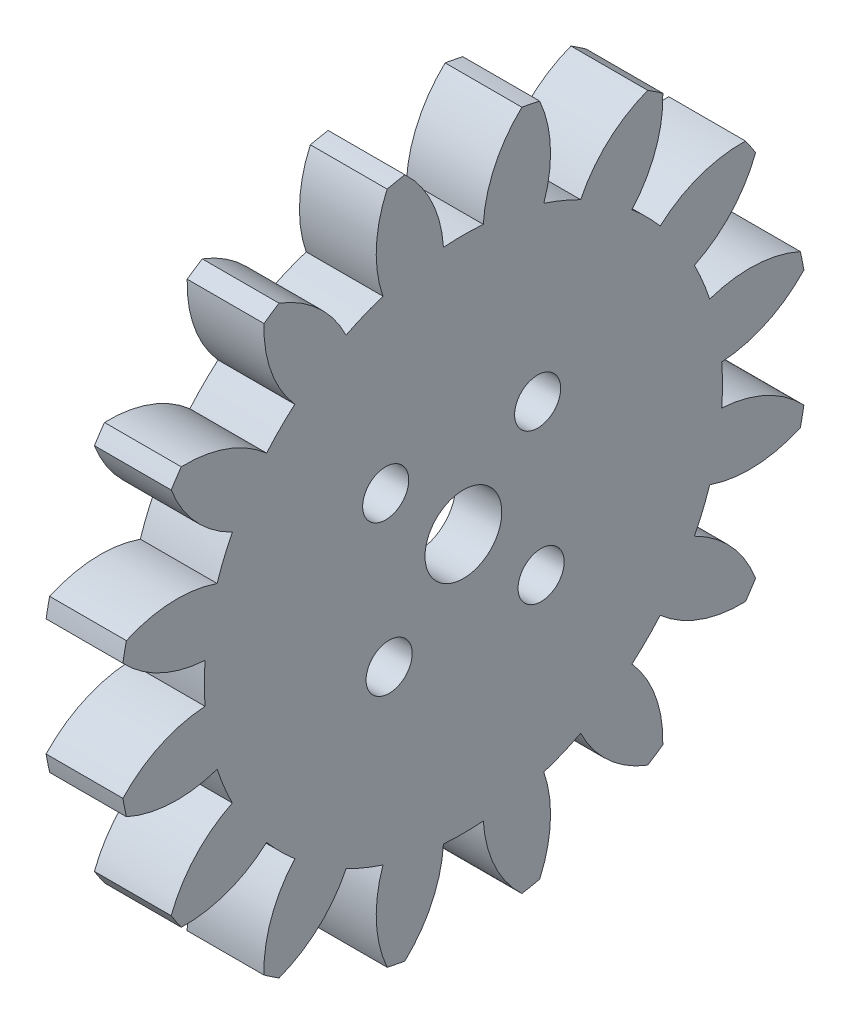
SolidWorks part; units mm, degrees
ref_plane "Plane1" through (0, 0, 0) normal (0, 0, 1) x (1, 0, 0)
ref_plane "Plane2" through (0, 0, 0) normal (0, 1, 0) x (1, 0, 0)
ref_plane "Plane3" through (0, 0, 0) normal (1, 0, 0) x (0, 0, -1)
other "Configuration Table"
sketch "HoldingSke" plane through (0, 0, 0) normal (0, 1, 0) x (1, 0, 0)
  line L0 (0, 0) -> (0.3845, -0.1103)
  line L1 (-15, 0) -> (100, 0) construction
  line L2 (0, 0) -> (-2.1039, 2.3779)
  line L3 (0, 0) -> (-11.863, 4.5341)
  line L4 (0, 0) -> (8.3015, 2.3804)
  line L5 (0, 0) -> (-46.8476, -17.4728)
  line L6 (0, 0) -> (-4.1448, -2.7965)
  line L7 (-2.1039, 2.3779) -> (8.6586, 51.2059)
  line L8 (-76.2, 54.61) -> (-75.3, 54.61)
  line L9 (-71.009, 38.7566) -> (-53.1078, 45.2721)
  line L10 (-76.2, 71.12) -> (104.1128, 71.12)
  line L11 (0, 0) -> (-5, 0)
  line L12 (-76.2, 101.6) -> (-76.113, 101.6)
  line L13 (24.9733, 27.94) -> (52.9518, 28.4284)
  line L14 (24.9733, 27.94) -> (24.9743, 27.94)
  line L15 (24.9733, 27.94) -> (100.4006, 29.5858)
  line L16 (-63.627, -2.5) -> (-12.827, -2.5)
  circle A0 centre (0, 0) radius 2.5
  circle A1 centre (0, 0) radius 16.874
  circle A2 centre (0, 0) radius 37.5
  circle A3 centre (0, 0) radius 2.5
  dimension "MHD" = 33.748
  dimension "Hub_dia" = 75
  dimension "Bore" = 5
  dimension "MBD" = 5
  dimension "Num_teeth" = 16
  dimension "Pitch" = 0.4
  dimension "Overall_len" = 50
  dimension "Show_teeth" = 16
  dimension "Thickness" = 5
  dimension "OAL" = 50.0001
  dimension "T_dim" = 0.9
  dimension "Ap" = 20
  dimension "H" = 19.05
  dimension "Pitch_radius" = 180.3128
  dimension "Width" = 5
  dimension "Backlash" = 0.087
  dimension "Addendum_fac" = 1
  dimension "Dedendum_fac" = 1.25
  dimension "Clearance_fac" = 0.25
  dimension "Dedendum_add" = 0.001
  dimension "Module" = 2.5
sketch "BasProSke" plane through (0, 0, 0) normal (0, 1, 0) x (1, 0, 0)
  line L0 (-10, 0) -> (60, 0) construction
  line L1 (0, 0) -> (0, 22.5)
  line L2 (0, 0) -> (5, 0)
  line L3 (5, 0) -> (5, 22.5)
  line L4 (5, 22.5) -> (0, 22.5)
  dimension "Thickness" = 5
  dimension "Diameter" = 45
revolve "Base-Revolve" add sketch "BasProSke" angle 360 about L0
sketch "TooCutSke" plane through (0, 0, 0) normal (1, 0, 0) x (0, 0, -1)
  line L1 (0, 0) -> (0, 107) construction
  line L2 (0, 0) -> (-2.1125, 19.8881) construction
  line L3 (0, 0) -> (-7.7717, 39.0708) construction
  line L4 (-2.1125, 19.8881) -> (-3.8858, 19.5354) construction
  arc A0 (1.2977, 16.824) -> (-1.2977, 16.824) centre (0, 0) ccw
  arc A1 (3.8326, 22.197) -> (-3.8326, 22.197) centre (0, 0) ccw
  circle A2 centre (0, 0) radius 20 construction
  circle A3 centre (0, 0) radius 18.7939 construction
  arc A4 (-1.2977, 16.824) -> (-3.8326, 22.197) centre (-9.2832, 16.3411) ccw
  arc A5 (3.8326, 22.197) -> (1.2977, 16.824) centre (9.2832, 16.3411) ccw
  dimension "Root_dia" = 33.748
  dimension "Overcut_dia" = 45.0508
  dimension "Pitch_dia" = 40
  dimension "Base_dia" = 37.5877
  dimension "Flank_rad" = 8
  dimension "Half_ang" = 11.25
  dimension "Half_CT" = 1.8081
extrude "ToothCut" cut sketch "TooCutSke" along normal through all
fillet "Breaks" [suppressed] radius 0.05
fillet "RootFillets" [suppressed] radius 0.626
pattern_circular "TeethCuts" count 16 every 22.5 about axis through (-10, 0, 0) along (1, 0, 0) of "ToothCut", "RootFillets", "Breaks"
sketch "HubNeaOneSke" plane through (0, 0, 0) normal (-1, 0, 0) x (0, 0, 1)
  circle A0 centre (0, 0) radius 16.874
  dimension "Diameter" = 33.748
extrude "HubNearOne" [suppressed] add sketch "HubNeaOneSke" along normal blind 45.0001
sketch "HubNeaBotSke" plane through (0, 0, 0) normal (-1, 0, 0) x (0, 0, 1)
  circle A0 centre (0, 0) radius 16.874
  dimension "Diameter" = 33.748
extrude "HubNearBoth" [suppressed] add sketch "HubNeaBotSke" along normal blind 22.5
ref_plane "FarPln" through (5, 0, 0) normal (1, 0, 0) x (0, 0, -1)
sketch "HubFarSke" plane through (5, 0, 0) normal (1, 0, 0) x (0, 0, -1)
  circle A0 centre (0, 0) radius 16.874
  dimension "Diameter" = 33.748
extrude "HubFar" [suppressed] add sketch "HubFarSke" along normal blind 22.5
sketch "BorSke" plane through (0, 0, 0) normal (1, 0, 0) x (0, 0, -1)
  circle A0 centre (0, 0) radius 2.5
  dimension "Diameter" = 5
extrude "Bore" cut sketch "BorSke" along normal mid plane 100.0001
sketch "KeySke" plane through (0, 0, 0) normal (1, 0, 0) x (0, 0, -1)
  line L0 (-1, 0) -> (-1, 3.4)
  line L1 (-1, 3.4) -> (1, 3.4)
  line L2 (1, 3.4) -> (1, 0)
  line L3 (0, 0) -> (0, 34) construction
  line L4 (-1, 0) -> (1, 0)
  dimension "Offset" = 3.4
  dimension "Width" = 2
extrude "Keyway" [suppressed] cut sketch "KeySke" along normal mid plane 100.0001
pattern_circular "Keyway2" [suppressed] count 2 every 90 about axis through (-10, 0, 0) along (1, 0, 0)
sketch "Esquisse3" plane through (5, 0, 0) normal (1, 0, 0) x (0, 0, -1)
  circle A0 centre (0, 0) radius 10
extrude "Enlèv. mat.-Extru.3" cut sketch "Esquisse3" against normal through all from offset 3 offset against normal yes
ref_plane "Plan1" through (-3.5, 1.318, 9.9128) normal (0, -0.9913, 0.1318) x (1, 0, 0)
sketch "Esquisse8" plane through (0, 0, 0) normal (-1, 0, 0) x (0, 0, 1)
  circle A0 centre (5.0609, 4.8361) radius 1.5
  circle A1 centre (-4.8361, 5.0609) radius 1.5
  circle A2 centre (4.8361, -5.0609) radius 1.5
  circle A3 centre (-5.0609, -4.8361) radius 1.5
extrude "Enlèv. mat.-Extru.4" cut sketch "Esquisse8" against normal through all
equation "' \"Module@HoldingSke\" = 6.35"
equation "' \"Num_teeth@HoldingSke\" = 12"
equation "' \"Ap@HoldingSke\" =  20"
equation "' \"Ap@HoldingSke\" = 20"
equation "' \"Width@HoldingSke\" = 0.5 * 25.4"
equation "' \"Hub_dia@HoldingSke\"= 1 * 25.4"
equation "' \"Hub_dia@HoldingSke\" = 1 * 25.4"
equation "' \"Overall_len@HoldingSke\" = 1.0 * 25.4"
equation "' \"Bore@HoldingSke\" = 0.75 * 25.4"
equation "' \"T_dim@HoldingSke\" = 0.1 * 25.4"
equation "' \"Width@KeySke\" = 0.25 * 25.4"
equation "' \"Show_teeth@HoldingSke\" = 13"
equation "' \"Backlash@HoldingSke\" = 0.009 * 25.4"
equation "' \"Addendum_fac@HoldingSke\" = 1.0"
equation "' \"Dedendum_fac@HoldingSke\" = 1.25"
equation "' \"Dedendum_add@HoldingSke\" = 0.00005 * 25.4"
equation "' \"Clearance_fac@HoldingSke\" = 0.25"
equation "\"Pitch@HoldingSke\" = 1 / \"Module@HoldingSke\""
equation "\"Overcut_dia@TooCutSke\" = (\"Num_teeth@HoldingSke\" + 2 * \"Addendum_fac@HoldingSke\") / \"Pitch@HoldingSke\" + 0.002 * 25.4"
equation "\"Pitch_dia@TooCutSke\" = \"Num_teeth@HoldingSke\" / \"Pitch@HoldingSke\""
equation "\"Base_dia@TooCutSke\" = \"Num_teeth@HoldingSke\" / \"Pitch@HoldingSke\" * cos((\"Ap@HoldingSke\"  * 3.14159265 / 180))"
equation "\"Root_dia@TooCutSke\" = (\"Num_teeth@HoldingSke\" + 2) / \"Pitch@HoldingSke\" - 2 * (\"Addendum_fac@HoldingSke\" + \"Dedendum_fac@HoldingSke\") / \"Pitch@HoldingSke\" - \"Dedendum_add@HoldingSke\" * 2"
equation "\"Half_ang@TooCutSke\" = 180 / \"Num_teeth@HoldingSke\""
equation "\"Half_CT@TooCutSke\" = \"Num_teeth@HoldingSke\" / \"Pitch@HoldingSke\" * sin((3.14159265 / 2 / \"Num_teeth@HoldingSke\")) / 2 - 7 * \"Backlash@HoldingSke\" / 4"
equation "\"Flank_rad@TooCutSke\" = \"Num_teeth@HoldingSke\" / \"Pitch@HoldingSke\" / 5"
equation "\"Radius@RootFillets\" = \"Clearance_fac@HoldingSke\" / \"Pitch@HoldingSke\" + \"Dedendum_add@HoldingSke\""
equation "\"Break_rad@Breaks\" = 0.02 / \"Pitch@HoldingSke\""
equation "\"Thickness@HoldingSke\" = \"Width@HoldingSke\""
equation "\"OAL@HoldingSke\" = \"Thickness@HoldingSke\""
equation "\"MHD@HoldingSke\" = (\"Num_teeth@HoldingSke\" + 2) / \"Pitch@HoldingSke\" - 2 * (\"Addendum_fac@HoldingSke\" + \"Dedendum_fac@HoldingSke\")  / \"Pitch@HoldingSke\" - \"Dedendum_add@HoldingSke\" * 2"
equation "\"MBD@HoldingSke\" = (\"Num_teeth@HoldingSke\" + 2) / \"Pitch@HoldingSke\" - 2 * (\"Addendum_fac@HoldingSke\" + \"Dedendum_fac@HoldingSke\")  / \"Pitch@HoldingSke\" - \"Dedendum_add@HoldingSke\" * 2 - 0.002 * 25.4"
equation "\"MHD@HoldingSke\" = ((sgn( \"MHD@HoldingSke\" - \"Hub_dia@HoldingSke\" )-1)*( \"MHD@HoldingSke\" - \"Hub_dia@HoldingSke\" ))/-2+ \"Hub_dia@HoldingSke\""
equation "\"MBD@HoldingSke\" = ((sgn( \"MBD@HoldingSke\" - \"Bore@HoldingSke\" )-1)*( \"MBD@HoldingSke\" - \"Bore@HoldingSke\" ))/-2+ \"Bore@HoldingSke\""
equation "\"OAL@HoldingSke\" = ((sgn( \"OAL@HoldingSke\" - \"Overall_len@HoldingSke\" )+1)*( \"OAL@HoldingSke\" - \"Overall_len@HoldingSke\" ))/2 + \"Overall_len@HoldingSke\" + 0.000002 * 25.4"
equation "\"Num_teeth@TeethCuts\" = int( \"Show_teeth@HoldingSke\" ) + 1"
equation "\"Num_teeth@TeethCuts\" = ((sgn( \"Num_teeth@TeethCuts\" - \"Num_teeth@HoldingSke\" )-1)*( \"Num_teeth@TeethCuts\" - \"Num_teeth@HoldingSke\" ))/-2+ \"Num_teeth@HoldingSke\""
equation "\"Num_teeth@TeethCuts\" = ((sgn( \"Num_teeth@TeethCuts\" - 2.0)+1)*( \"Num_teeth@TeethCuts\" - 2.0))/2 +2.0"
equation "\"Angle@TeethCuts\" = 360.0 / \"Num_teeth@HoldingSke\""
equation "\"Diameter@BasProSke\" = (\"Num_teeth@HoldingSke\" + 2 * \"Addendum_fac@HoldingSke\") / \"Pitch@HoldingSke\""
equation "\"Thickness@BasProSke\"  = \"Thickness@HoldingSke\""
equation "' \"Fillet_rad@BasProSke\" =  \"Thickness@HoldingSke\" * 0.05"
equation "' \"Fillet_rad@BasProSke\" = \"Thickness@HoldingSke\" * 0.05"
equation "\"MHD@HoldingSke\" = ((sgn( \"MHD@HoldingSke\" - \"Root_dia@TooCutSke\" )-1)*( \"MHD@HoldingSke\" - \"Root_dia@TooCutSke\" ))/-2+ \"Root_dia@TooCutSke\""
equation "\"Diameter@HubNeaOneSke\" = \"MHD@HoldingSke\""
equation "\"Length@HubNearOne\" = \"OAL@HoldingSke\" - \"Thickness@BasProSke\""
equation "\"Diameter@HubNeaBotSke\" = \"MHD@HoldingSke\""
equation "\"Length@HubNearBoth\" = ( \"OAL@HoldingSke\" - \"Thickness@BasProSke\" ) / 2.0"
equation "\"Thickness@FarPln\" = \"Thickness@BasProSke\""
equation "\"Diameter@HubFarSke\" = \"MHD@HoldingSke\""
equation "\"Length@HubFar\" = ( \"OAL@HoldingSke\" - \"Thickness@BasProSke\" ) / 2.0"
equation "\"Diameter@BorSke\" = \"MBD@HoldingSke\""
equation "\"D1@Bore\" = \"OAL@HoldingSke\" * 2.0"
equation "\"D1@Keyway\" = \"OAL@HoldingSke\" * 2.0"
equation "\"Offset@KeySke\" = \"T_dim@HoldingSke\" + \"MBD@HoldingSke\" / 2.0"
